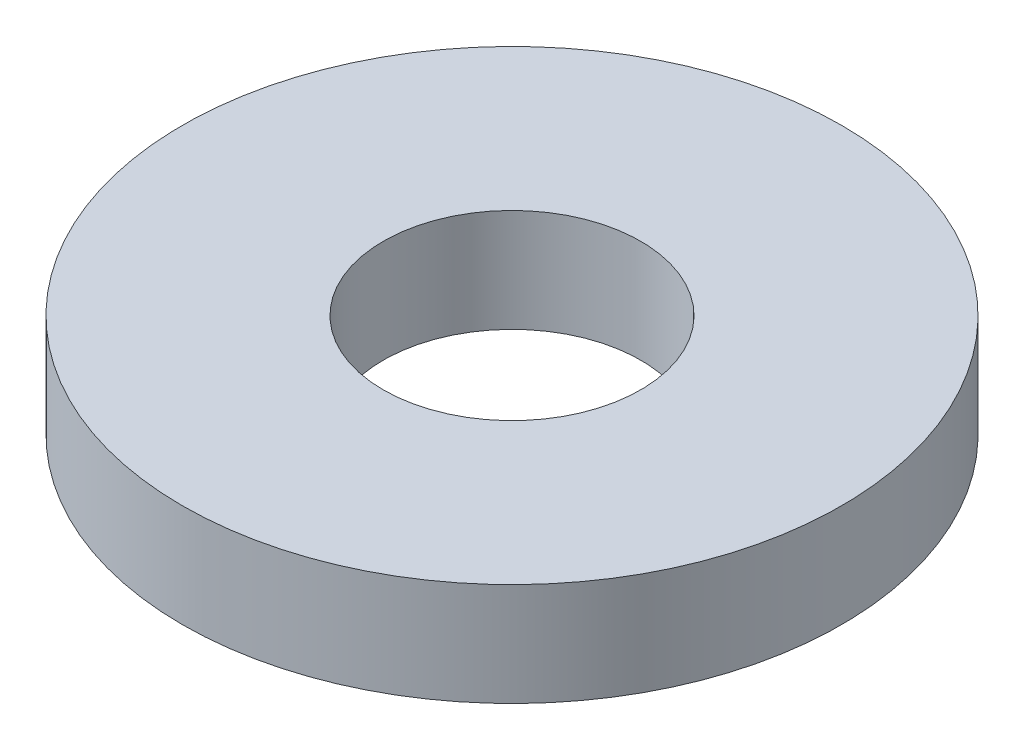
SolidWorks part; units mm, degrees
ref_plane "Front Plane" through (0, 0, 0) normal (0, 0, 1) x (1, 0, 0)
ref_plane "Top Plane" through (0, 0, 0) normal (0, 1, 0) x (1, 0, 0)
ref_plane "Right Plane" through (0, 0, 0) normal (1, 0, 0) x (0, 0, -1)
sketch "Sketch1" plane through (0, 0, 0) normal (0, 1, 0) x (1, 0, 0)
  circle A0 centre (0, 0) radius 3.175
  circle A1 centre (0, 0) radius 8.128
  dimension "D1" = 6.35
  dimension "D2" = 16.256
extrude "Boss-Extrude1" add sketch "Sketch1" along normal blind 2.54
